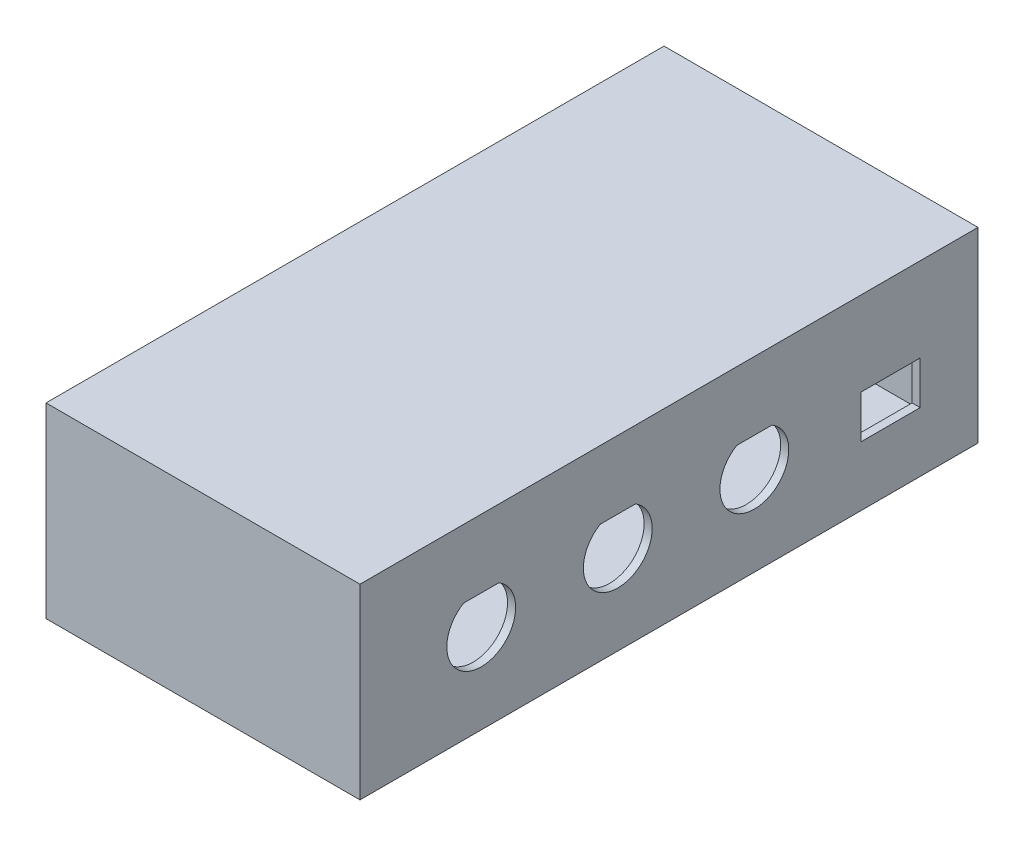
SolidWorks part; units mm, degrees
ref_plane "Front Plane" through (0, 0, 0) normal (0, 0, 1) x (1, 0, 0)
ref_plane "Top Plane" through (0, 0, 0) normal (0, 1, 0) x (1, 0, 0)
ref_plane "Right Plane" through (0, 0, 0) normal (1, 0, 0) x (0, 0, -1)
sketch "Sketch1" plane through (0, 0, 0) normal (0, 1, 0) x (1, 0, 0)
  line L0 (-1001.7514, -31.6356) -> (-1001.7514, 76.3144) construction
  line L1 (-1058.5514, -33.6356) -> (-1001.6514, -33.6356)
  line L2 (-1058.5514, -33.6356) -> (-1058.5514, 78.3144)
  line L3 (-1058.5514, 78.3144) -> (-1001.6514, 78.3144)
  line L4 (-1001.6514, -33.6356) -> (-1001.6514, 78.3144)
  line L5 (-1058.5514, -33.6356) -> (-1001.6514, 78.3144) construction
  line L6 (-1058.5514, 78.3144) -> (-1001.6514, -33.6356) construction
  line L7 (-1058.5514, 79.8144) -> (-1058.5514, -35.1356) construction
  line L10 (-1001.7514, 76.3144) -> (-1055.7264, 76.3144) construction
  line L12 (-1055.7264, -31.6356) -> (-1001.7514, -31.6356) construction
  point P0 (-1030.1014, 22.3394)
  dimension "D1" = 2
  dimension "D2" = 0.1
  dimension "D3" = 2
extrude "MainBody" add sketch "Sketch1" along normal blind 31.75
shell "Shell1" thickness 1.5
ref_plane "BottomInside" through (0, -1.5, 0) normal (0, -1, 0) x (-1, 0, 0)
ref_plane "LeftInside" through (-1058.5514, 0, 0) normal (-1, 0, 0) x (0, 0, 1)
ref_plane "FrontInside" through (0, 0, -78.3144) normal (0, 0, 1) x (1, 0, 0)
ref_plane "RightInside" through (-1001.6514, 0, 0) normal (-1, 0, 0) x (0, 0, 1)
ref_plane "MidPlane" through (0, 0, -22.3394) normal (0, 0, 1) x (1, 0, 0)
sketch "Sketch3" plane through (-1000.1514, 0, 0) normal (1, 0, 0) x (0, 0, -1)
  line L0 (-15.8582, 20.5613) -> (-9.313, 20.5613)
  line L1 (-12.5856, 8.6613) -> (-25.0542, 8.6613) construction
  line L2 (9.5418, 20.5613) -> (16.087, 20.5613)
  line L3 (34.9418, 20.5613) -> (41.487, 20.5613)
  arc A0 (-15.8582, 20.5613) -> (-9.313, 20.5613) centre (-12.5856, 15.0613) ccw
  arc A1 (9.5418, 20.5613) -> (16.087, 20.5613) centre (12.8144, 15.0613) ccw
  arc A2 (34.9418, 20.5613) -> (41.487, 20.5613) centre (38.2144, 15.0613) ccw
  point P12 (38.2144, 15.0613)
  point P14 (12.8144, 15.0613)
  dimension "D2" = 6.4
  dimension "D1" = 11.9
sketch "Sketch4" plane through (-1000.1514, 0, 0) normal (1, 0, 0) x (0, 0, -1)
  line L1 (58.0547, 17.5941) -> (69.0547, 17.5941)
  line L2 (58.0547, 17.5941) -> (58.0547, 9.5941)
  line L3 (58.0547, 9.5941) -> (69.0547, 9.5941)
  line L4 (69.0547, 17.5941) -> (69.0547, 9.5941)
  line L8 (63.5938, 14.9191) -> (63.5938, 12.2691) construction
  line L11 (60.5938, 14.9142) -> (66.5938, 14.9239) construction
  line L12 (63.2426, 12.2685) -> (64.0126, 12.2697) construction
  line L13 (61.2021, 12.2652) -> (63.3831, 12.2687) construction
  line L14 (63.8131, 12.2694) -> (65.9941, 12.2729) construction
  point P10 (63.5938, 13.5941)
  point P11 (58.0547, 13.5941)
  dimension "D1" = 11
  dimension "D2" = 8
extrude "USBCutout" cut sketch "Sketch4" against normal up to next
extrude "BNCCutout" cut sketch "Sketch3" against normal up to next
